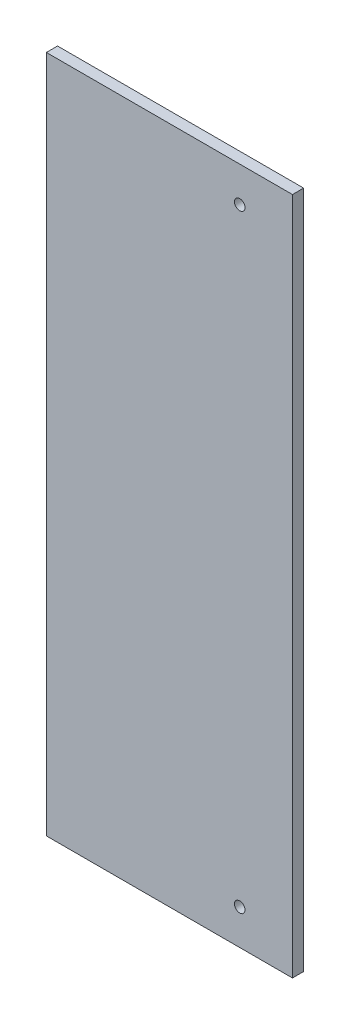
SolidWorks part; units mm, degrees
ref_plane "Front Plane" through (0, 0, 0) normal (0, 0, 1) x (1, 0, 0)
ref_plane "Top Plane" through (0, 0, 0) normal (0, 1, 0) x (1, 0, 0)
ref_plane "Right Plane" through (0, 0, 0) normal (1, 0, 0) x (0, 0, -1)
sketch "Sketch1" plane through (0, 0, 0) normal (0, 0, 1) x (1, 0, 0)
  line L1 (0, 0) -> (70, 0)
  line L2 (0, 0) -> (0, 193)
  line L3 (0, 193) -> (70, 193)
  line L4 (70, 0) -> (70, 193)
  circle A0 centre (55, 183) radius 1.5
  circle A1 centre (55, 10) radius 1.5
  point P9 (0, 0)
  point P10 (0, 0)
  point P11 (0, 0)
  point P12 (70, 18.2342)
  dimension "D5" = 3
  dimension "D1" = 193
  dimension "D2" = 70
  dimension "D3" = 173
  dimension "D4" = 10
  dimension "D6" = 15
  dimension "D7" = 15
extrude "Boss-Extrude1" add sketch "Sketch1" along normal blind 3.175
